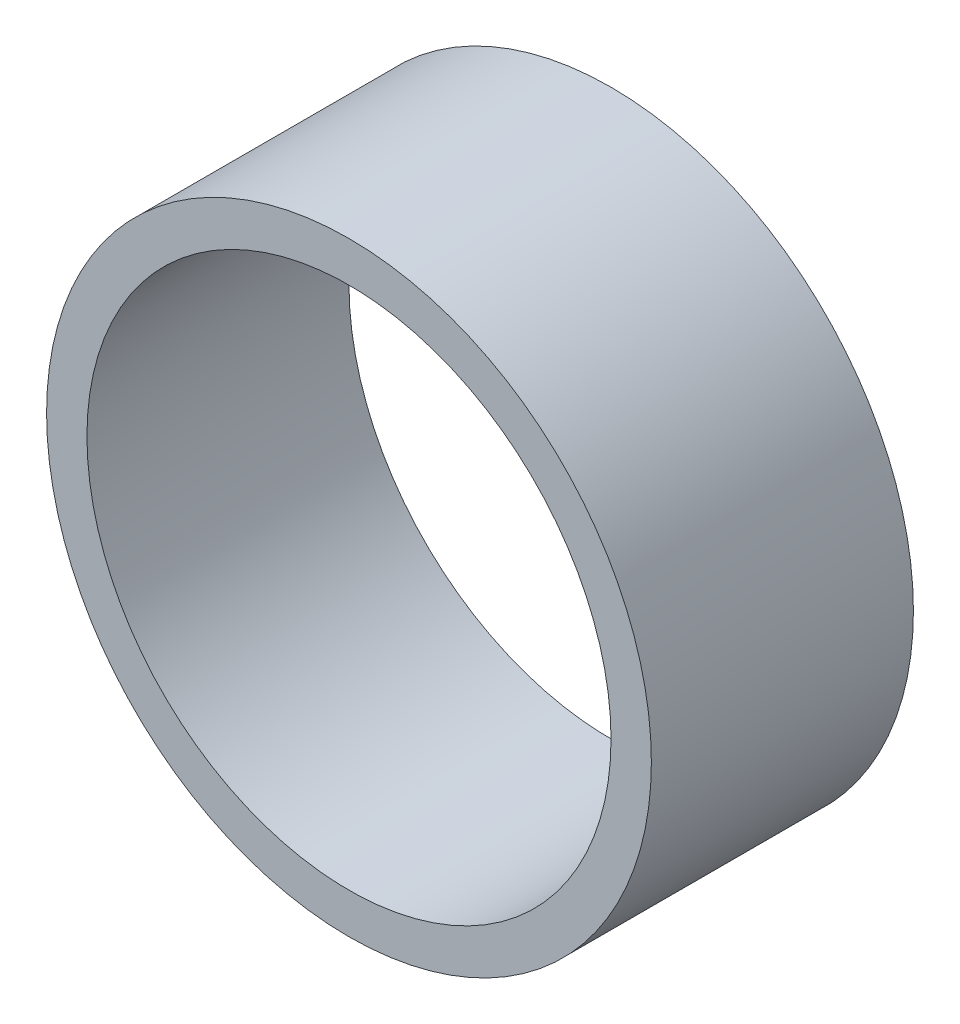
SolidWorks part; units mm, degrees
ref_plane "Front Plane" through (0, 0, 0) normal (0, 0, 1) x (1, 0, 0)
ref_plane "Top Plane" through (0, 0, 0) normal (0, 1, 0) x (1, 0, 0)
ref_plane "Right Plane" through (0, 0, 0) normal (1, 0, 0) x (0, 0, -1)
sketch "Sketch1" plane through (0, 0, 0) normal (0, 0, 1) x (1, 0, 0)
  circle A0 centre (0, 0) radius 11.54
  circle A1 centre (0, 0) radius 10
  dimension "D1" = 23.08
  dimension "D2" = 20
extrude "Boss-Extrude1" add sketch "Sketch1" along normal blind 10
